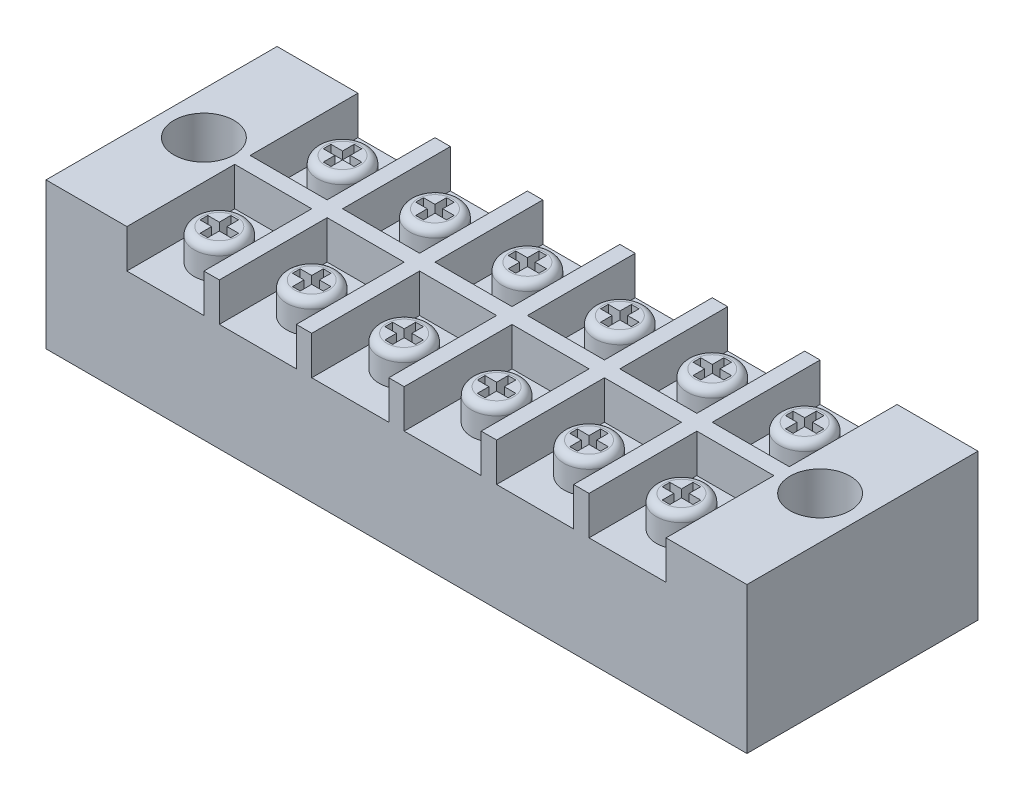
SolidWorks part; units mm, degrees
ref_plane "前视基准面" through (0, 0, 0) normal (0, 0, 1) x (1, 0, 0)
ref_plane "上视基准面" through (0, 0, 0) normal (0, 1, 0) x (1, 0, 0)
ref_plane "右视基准面" through (0, 0, 0) normal (1, 0, 0) x (0, 0, -1)
sketch "草图1" plane through (0, 0, 0) normal (0, 1, 0) x (1, 0, 0)
  line L1 (45.5, -15) -> (-45.5, -15)
  line L2 (45.5, -15) -> (45.5, 15)
  line L3 (45.5, 15) -> (-45.5, 15)
  line L4 (-45.5, -15) -> (-45.5, 15)
  line L5 (45.5, -15) -> (-45.5, 15) construction
  line L6 (45.5, 15) -> (-45.5, -15) construction
  point P0 (0, 0)
  dimension "D1" = 91
  dimension "D2" = 30
extrude "凸台-拉伸1" add sketch "草图1" along normal blind 19 contours L3 L4 L1 L2
sketch "草图2" plane through (0, 19, 0) normal (0, 1, 0) x (1, 0, 0)
  line L0 (0, 0) -> (0, 8.3631) construction
  circle A0 centre (-40, 0) radius 2.15
  circle A1 centre (40, 0) radius 2.15
  dimension "D1" = 4.3
  dimension "D2" = 40
extrude "切除-拉伸1" cut sketch "草图2" against normal through all
sketch "草图3" plane through (0, 19, 0) normal (0, 1, 0) x (1, 0, 0)
  line L0 (45.5, 15) -> (-45.5, 15) construction
  line L1 (-35, 15) -> (-25, 15)
  line L2 (-35, 15) -> (-35, 1)
  line L3 (-35, 1) -> (-25, 1)
  line L4 (-25, 15) -> (-25, 1)
  line L5 (0, 0) -> (0, 21.059) construction
  line L6 (-23, 15) -> (-13, 15)
  line L7 (-23, 15) -> (-23, 1)
  line L8 (-23, 1) -> (-13, 1)
  line L9 (-13, 15) -> (-13, 1)
  line L10 (-11, 15) -> (-1, 15)
  line L11 (-11, 15) -> (-11, 1)
  line L12 (-11, 1) -> (-1, 1)
  line L13 (-1, 15) -> (-1, 1)
  line L14 (0, 0) -> (33.7118, 0) construction
  line L15 (-1, -15) -> (-1, -1)
  line L16 (-11, -1) -> (-1, -1)
  line L17 (-11, -15) -> (-11, -1)
  line L18 (-11, -15) -> (-1, -15)
  line L19 (-13, -15) -> (-13, -1)
  line L20 (-23, -1) -> (-13, -1)
  line L21 (-23, -15) -> (-23, -1)
  line L22 (-23, -15) -> (-13, -15)
  line L23 (-25, -15) -> (-25, -1)
  line L24 (-35, -1) -> (-25, -1)
  line L25 (-35, -15) -> (-35, -1)
  line L26 (-35, -15) -> (-25, -15)
  line L27 (35, -15) -> (25, -15)
  line L28 (35, -15) -> (35, -1)
  line L29 (35, -1) -> (25, -1)
  line L30 (25, -15) -> (25, -1)
  line L31 (23, -15) -> (13, -15)
  line L32 (23, -15) -> (23, -1)
  line L33 (23, -1) -> (13, -1)
  line L34 (13, -15) -> (13, -1)
  line L35 (11, -15) -> (1, -15)
  line L36 (11, -15) -> (11, -1)
  line L37 (11, -1) -> (1, -1)
  line L38 (1, -15) -> (1, -1)
  line L39 (1, 15) -> (1, 1)
  line L40 (11, 1) -> (1, 1)
  line L41 (11, 15) -> (11, 1)
  line L42 (11, 15) -> (1, 15)
  line L43 (13, 15) -> (13, 1)
  line L44 (23, 1) -> (13, 1)
  line L45 (23, 15) -> (23, 1)
  line L46 (23, 15) -> (13, 15)
  line L47 (25, 15) -> (25, 1)
  line L48 (35, 1) -> (25, 1)
  line L49 (35, 15) -> (35, 1)
  line L50 (35, 15) -> (25, 15)
  dimension "D1" = 10
  dimension "D2" = 10
  dimension "D3" = 2
  dimension "D4" = 1
  dimension "D5" = 2
  dimension "D6" = 10
  dimension "D7" = 1
extrude "切除-拉伸2" cut sketch "草图3" against normal blind 5
sketch "草图4" plane through (0, 19, 0) normal (0, 1, 0) x (1, 0, 0)
  line L0 (0, 0) -> (0, 8.0248) construction
  circle A0 centre (-40, 0) radius 3.9
  circle A1 centre (40, 0) radius 3.9
  dimension "D1" = 7.8
extrude "切除-拉伸3" cut sketch "草图4" against normal blind 13.6
sketch "草图5" plane through (0, 14, 0) normal (0, 1, 0) x (1, 0, 0)
  line L0 (-35, 1) -> (-25, 1) construction
  line L1 (-25, 1) -> (-25, 15) construction
  line L2 (-30.125, 8.5) -> (-29.875, 8.5) construction
  line L3 (-29.5, 6) -> (-30.5, 6)
  line L4 (-29.5, 6) -> (-29.5, 7.5)
  line L5 (-29.5, 10) -> (-30.5, 10)
  line L6 (-30.5, 6) -> (-30.5, 7.5)
  line L7 (-29.5, 6) -> (-30.5, 10) construction
  line L8 (-29.5, 10) -> (-30.5, 6) construction
  line L9 (-32, 7.5) -> (-30.5, 7.5)
  line L10 (-32, 7.5) -> (-32, 8.5)
  line L11 (-32, 8.5) -> (-30.5, 8.5)
  line L12 (-28, 7.5) -> (-28, 8.5)
  line L13 (-32, 7.5) -> (-28, 8.5) construction
  line L14 (-32, 8.5) -> (-28, 7.5) construction
  line L15 (-30.5, 8.5) -> (-30.5, 10)
  line L16 (-29.5, 8.5) -> (-28, 8.5)
  line L17 (-29.5, 8.5) -> (-29.5, 10)
  line L18 (-29.5, 7.875) -> (-29.5, 8.125) construction
  line L19 (-29.5, 7.5) -> (-28, 7.5)
  line L20 (-30.125, 7.5) -> (-29.875, 7.5) construction
  line L21 (-30.5, 7.875) -> (-30.5, 8.125) construction
  circle A0 centre (-30, 8) radius 3.25
  point P5 (-30, 1)
  point P9 (-25, 8)
  dimension "D1" = 6.5
  dimension "D2" = 1
  dimension "D3" = 1
  dimension "D4" = 4
  dimension "D5" = 4
extrude "凸台-拉伸2" add sketch "草图5" along normal blind 4
fillet "圆角1" radius 1 1 edges at (-30, 18, -4.75)
sketch "草图6" plane through (0, 14, 0) normal (0, 1, 0) x (1, 0, 0)
  line L12 (-28, 8.5) -> (-29.5, 8.5)
  line L13 (-29.5, 8.5) -> (-29.5, 10)
  line L14 (-29.5, 10) -> (-30.5, 10)
  line L15 (-30.5, 10) -> (-30.5, 8.5)
  line L16 (-30.5, 8.5) -> (-32, 8.5)
  line L17 (-32, 8.5) -> (-32, 7.5)
  line L18 (-32, 7.5) -> (-30.5, 7.5)
  line L19 (-30.5, 7.5) -> (-30.5, 6)
  line L20 (-30.5, 6) -> (-29.5, 6)
  line L21 (-29.5, 6) -> (-29.5, 7.5)
  line L22 (-29.5, 7.5) -> (-28, 7.5)
  line L23 (-28, 7.5) -> (-28, 8.5)
  line L24 (-28, 8.5) -> (-29.5, 8.5)
  line L25 (-29.5, 8.5) -> (-29.5, 10)
  line L26 (-29.5, 10) -> (-30.5, 10)
  line L27 (-30.5, 10) -> (-30.5, 8.5)
  line L28 (-30.5, 8.5) -> (-32, 8.5)
  line L29 (-32, 8.5) -> (-32, 7.5)
  line L30 (-32, 7.5) -> (-30.5, 7.5)
  line L31 (-30.5, 7.5) -> (-30.5, 6)
  line L32 (-30.5, 6) -> (-29.5, 6)
  line L33 (-29.5, 6) -> (-29.5, 7.5)
  line L34 (-29.5, 7.5) -> (-28, 7.5)
  line L35 (-28, 7.5) -> (-28, 8.5)
  dimension "D1" = 0
extrude "凸台-拉伸3" add sketch "草图6" along normal blind 3
pattern_linear "阵列(线性)1" count 6 spacing 12 along (1, 0, 0) count 2 spacing 16 along (0, 0, 1) of "凸台-拉伸2", "圆角1"
